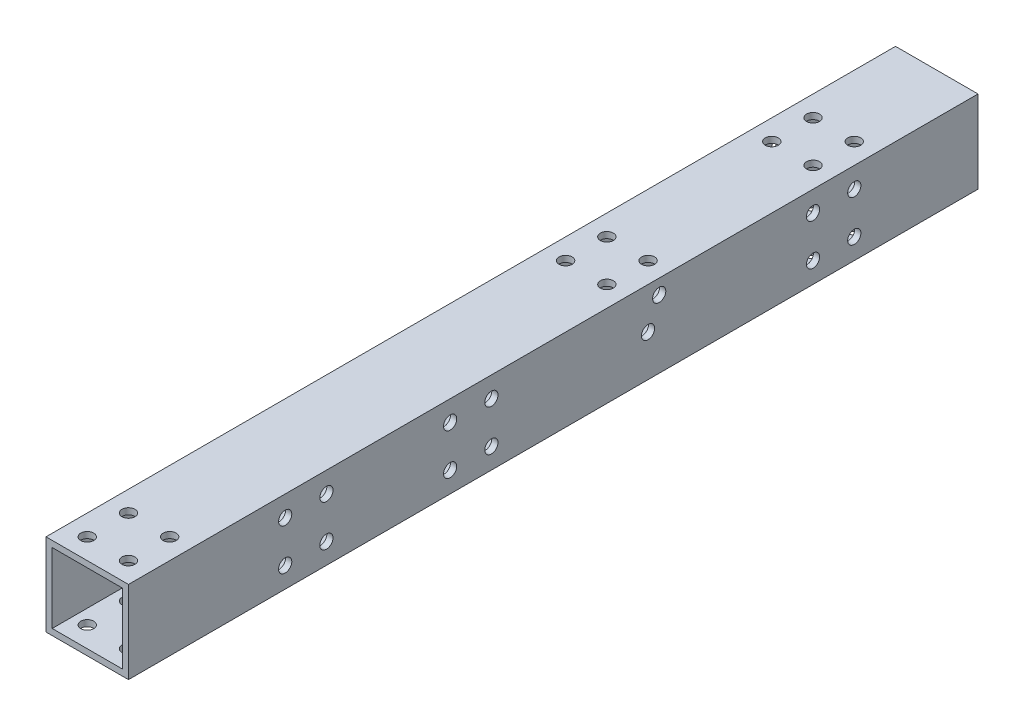
SolidWorks part; units mm, degrees
ref_plane "前视基准面" through (0, 0, 0) normal (0, 0, 1) x (1, 0, 0)
ref_plane "上视基准面" through (0, 0, 0) normal (0, 1, 0) x (1, 0, 0)
ref_plane "右视基准面" through (0, 0, 0) normal (1, 0, 0) x (0, 0, -1)
other "Configuration Table"
sketch "草图1" plane through (0, 0, 0) normal (0, 0, 1) x (1, 0, 0)
  line L1 (0, 0) -> (20, 0)
  line L2 (0, 0) -> (0, -20)
  line L3 (0, -20) -> (20, -20)
  line L4 (20, 0) -> (20, -20)
  dimension "D1" = 20
  dimension "D2" = 20
extrude "拉伸-薄壁1" add sketch "草图1" along normal blind 206 thin
sketch "草图2" plane through (0, 0, 0) normal (0, 1, 0) x (1, 0, 0)
  line L0 (20, -206) -> (0, -206) construction
  line L1 (0, -206) -> (0, 0) construction
  line L2 (20, -206) -> (20, 0) construction
  line L3 (0, -103) -> (20, -103) construction
  line L4 (20, 0) -> (0, 0) construction
  line L5 (0, -80) -> (20, -80) construction
  line L6 (10, -206) -> (10, -196) construction
  line L7 (0, -196) -> (20, -196) construction
  line L9 (10, 0) -> (10, -30) construction
  line L10 (0, -30) -> (20, -30) construction
  line L11 (0, -55) -> (20, -55) construction
  circle A5 centre (5, -191) radius 1.575
  circle A6 centre (15, -191) radius 1.575
  circle A7 centre (15, -201) radius 1.575
  circle A8 centre (5, -201) radius 1.575
  circle A10 centre (5, -25) radius 1.575
  circle A14 centre (15, -25) radius 1.575
  circle A15 centre (15, -35) radius 1.575
  circle A16 centre (5, -35) radius 1.575
  circle A17 centre (5, -75) radius 1.575
  circle A18 centre (15, -75) radius 1.575
  circle A19 centre (15, -85) radius 1.575
  circle A20 centre (5, -85) radius 1.575
  point P11 (10, 0)
  dimension "D2" = 5
  dimension "D4" = 3.15
  dimension "D7" = 3.15
  dimension "D1" = 5
  dimension "D3" = 10
  dimension "D5" = 30
  dimension "D6" = 25
  dimension "D8" = 5
  dimension "D9" = 5
extrude "切除-拉伸1" cut sketch "草图2" against normal through all
sketch "草图3" plane through (0, 0, 0) normal (-1, 0, 0) x (0, 0, 1)
  line L0 (143, 0) -> (143, -20) construction
  line L1 (206, 0) -> (0, 0) construction
  line L2 (206, -20) -> (0, -20) construction
  line L3 (0, 0) -> (0, -20) construction
  line L4 (123, 0) -> (123, -20) construction
  line L5 (0, -10) -> (206, -10) construction
  line L6 (206, 0) -> (206, -20) construction
  line L7 (163, 0) -> (163, -20) construction
  line L8 (35, 0) -> (35, -20) construction
  line L9 (80, -10) -> (75, -10) construction
  line L10 (75, -10) -> (75, 2) construction
  line L11 (75, 2) -> (80, -10) construction
  circle A0 centre (118, -5) radius 1.6
  circle A1 centre (128, -5) radius 1.6
  circle A2 centre (128, -15) radius 1.6
  circle A3 centre (118, -15) radius 1.6
  circle A4 centre (168, -15) radius 1.6
  circle A5 centre (158, -15) radius 1.6
  circle A6 centre (158, -5) radius 1.6
  circle A7 centre (168, -5) radius 1.6
  circle A8 centre (30, -5) radius 1.6
  circle A9 centre (40, -5) radius 1.6
  circle A10 centre (40, -15) radius 1.6
  circle A11 centre (30, -15) radius 1.6
  circle A12 centre (80, -10) radius 1.6
  circle A13 centre (77.3077, -3.5385) radius 1.6
  dimension "D3" = 3.2
  dimension "D7" = 3.2
  dimension "D10" = 3.2
  dimension "D14" = 3.2
  dimension "D1" = 143
  dimension "D2" = 20
  dimension "D4" = 5
  dimension "D5" = 5
  dimension "D6" = 35
  dimension "D8" = 5
  dimension "D9" = 5
  dimension "D11" = 80
  dimension "D12" = 5
  dimension "D13" = 12
  dimension "D15" = 7
extrude "切除-拉伸2" cut sketch "草图3" against normal through all
